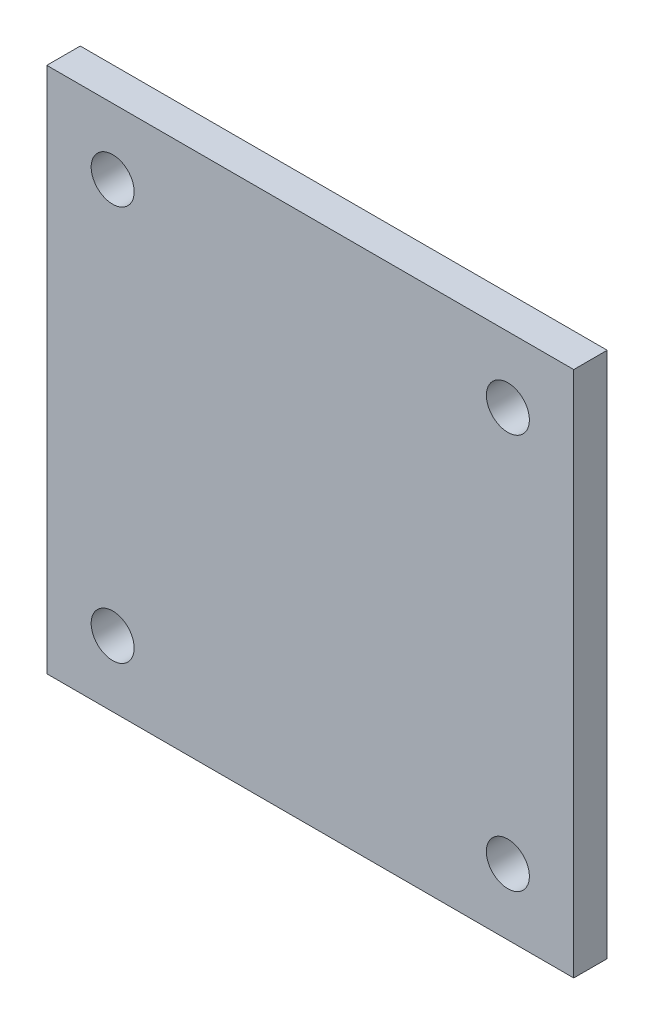
SolidWorks part; units mm, degrees
ref_plane "Front Plane" through (0, 0, 0) normal (0, 0, 1) x (1, 0, 0)
ref_plane "Top Plane" through (0, 0, 0) normal (0, 1, 0) x (1, 0, 0)
ref_plane "Right Plane" through (0, 0, 0) normal (1, 0, 0) x (0, 0, -1)
sketch "Sketch1" plane through (0, 0, 0) normal (0, 0, 1) x (1, 0, 0)
  line L1 (-20, 20) -> (20, 20)
  line L2 (-20, 20) -> (-20, -20)
  line L3 (-20, -20) -> (20, -20)
  line L4 (20, 20) -> (20, -20)
  line L5 (-20, 20) -> (20, -20) construction
  line L6 (-20, -20) -> (20, 20) construction
  point P0 (0, 0)
  dimension "D1" = 40
  dimension "D2" = 40
extrude "Boss-Extrude1" add sketch "Sketch1" along normal blind 2.54
hole_wizard "#4 Clearance Hole1" positions "Sketch3" profile "Sketch2" hole size "#4" standard "ANSI Inch" end condition through all
sketch "Sketch3" plane through (0, 0, 2.54) normal (0, 0, 1) x (1, 0, 0)
  line L0 (-20, 20) -> (-20, -20) construction
  line L2 (20, 20) -> (-20, 20) construction
  line L3 (0, 20) -> (0, -20) construction
  line L4 (-20, -20) -> (20, -20) construction
  line L6 (-20, 0) -> (20, 0) construction
  line L7 (20, -20) -> (20, 20) construction
  point P0 (-15, 15)
  point P33 (15, 15)
  point P40 (15, -15)
  point P41 (-15, -15)
  dimension "D1" = 5
  dimension "D2" = 5
sketch "Sketch2" plane through (-15, 15, 2.54) normal (1, 0, 0) x (0, -1, 0)
  line L0 (0, 0) -> (0, 2.54)
  line L1 (0, 2.54) -> (1.6319, 2.54)
  line L2 (1.6319, 2.54) -> (1.6319, 0)
  line L5 (1.6319, 0) -> (0, 0)
  line L11 (0, -6.35) -> (0, 107.95) construction
  dimension "Thru Hole Dia." = 3.2639
  dimension "Thru Hole Depth" = 2.54
